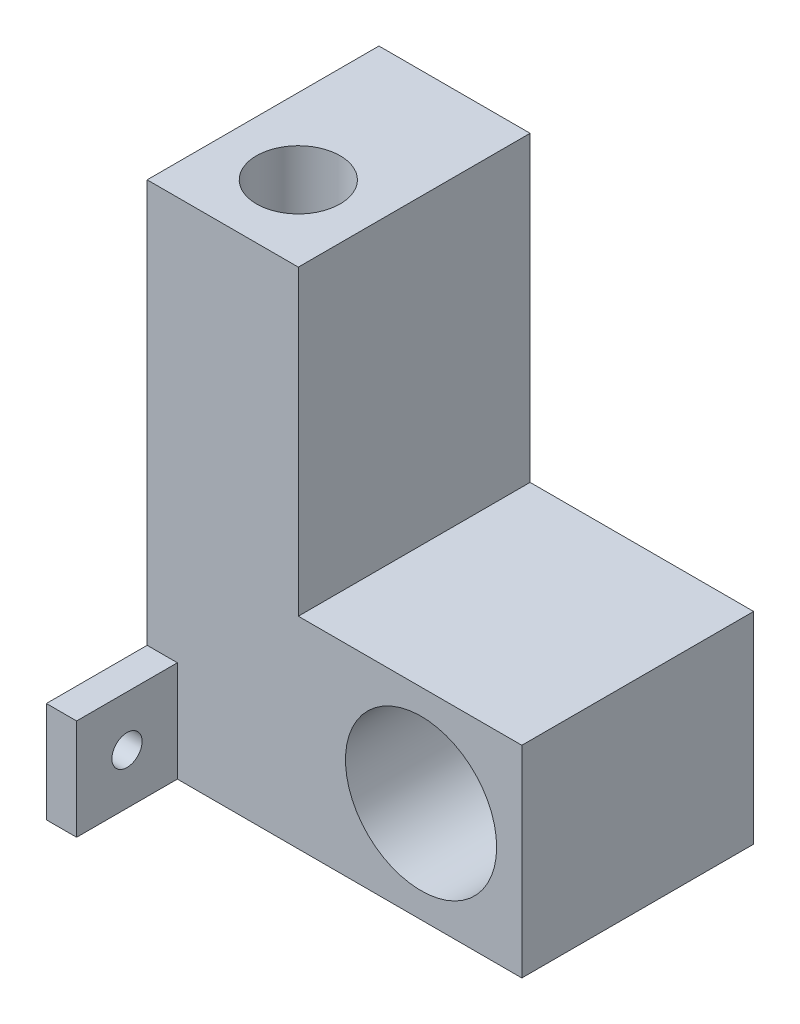
SolidWorks part; units mm, degrees
ref_plane "Front Plane" through (0, 0, 0) normal (0, 0, 1) x (1, 0, 0)
ref_plane "Top Plane" through (0, 0, 0) normal (0, 1, 0) x (1, 0, 0)
ref_plane "Right Plane" through (0, 0, 0) normal (1, 0, 0) x (0, 0, -1)
sketch "Sketch1" plane through (0, 0, 0) normal (0, 0, 1) x (1, 0, 0)
  line L0 (-12.1801, -10) -> (150.2507, -10) construction
  line L1 (0, 0) -> (200.754, 0) construction
  line L3 (0, 121.8331) -> (200.754, 121.8331) construction
  line L4 (200.754, 0) -> (200.754, 121.8331) construction
  line L5 (-12.1801, -10) -> (10, -10)
  line L6 (-12.1801, -10) -> (-12.1801, 10)
  line L7 (-12.1801, 10) -> (10, 10)
  line L8 (10, -10) -> (10, 10)
  line L10 (-12.1801, 10) -> (10, 10)
  line L18 (41.5355, 68.3037) -> (44.4022, 68.3037)
  line L19 (41.5355, 68.3037) -> (41.5355, 71.1731)
  line L20 (41.5355, 71.1731) -> (44.4022, 71.1731)
  line L21 (44.4022, 68.3037) -> (44.4022, 71.1731)
  line L22 (-12.1801, -10) -> (-27.1801, -10)
  line L23 (-12.1801, -10) -> (-12.1801, 40)
  line L24 (-12.1801, 40) -> (-27.1801, 40)
  line L25 (-27.1801, -10) -> (-27.1801, 40)
  circle A0 centre (0, 0) radius 7.5
  circle A1 centre (0, 0) radius 10
  circle A2 centre (0, 42.5) radius 32.5 construction
  circle A3 centre (14.5359, 39.9369) radius 32.5 construction
  circle A4 centre (27.3185, 32.5569) radius 32.5 construction
  circle A5 centre (36.8061, 21.25) radius 32.5 construction
  circle A6 centre (41.5355, 68.3037) radius 8
  circle A7 centre (41.5355, 68.3037) radius 14.65
  circle A8 centre (56.8061, 21.25) radius 32.5 construction
  circle A9 centre (76.8061, 21.25) radius 32.5 construction
  circle A10 centre (96.8061, 21.25) radius 32.5 construction
  circle A11 centre (116.8061, 21.25) radius 32.5 construction
  point P22 (0, 0)
  dimension "D1" = 15
  dimension "D3" = 20
  dimension "D8" = 65
  dimension "D10" = 16
  dimension "D11" = 29.3
  dimension "D2" = 0
  dimension "D4" = 10
  dimension "D5" = 15
  dimension "D6" = 50
  dimension "D7" = 10
  dimension "D12" = 5
  dimension "D9" = 4
extrude "Boss-Extrude1" add sketch "Sketch1" along normal blind 23 contours L25 L22 L6 L23 L24 | A1 L7 L6 L5 | A1 L5 L8 | A1 L8 L10 | A0
sketch "Sketch2" plane through (0, 40, 0) normal (0, 1, 0) x (1, 0, 0)
  line L0 (-12.1801, -23) -> (-27.1801, -23) construction
  line L1 (-12.1801, -23) -> (-12.1801, 0) construction
  circle A0 centre (-19.6801, -15.5) radius 4.15
  dimension "D1" = 7.5
  dimension "D3" = 8.3
  dimension "D2" = 7.5
extrude "Cut-Extrude1" cut sketch "Sketch2" against normal through all
sketch "Sketch3" plane through (-27.1801, 0, 0) normal (-1, 0, 0) x (0, 0, 1)
  line L0 (23, 40) -> (0, 40) construction
  line L1 (-10, -10) -> (33, -10)
  line L2 (-10, -10) -> (-10, 0)
  line L3 (-10, 0) -> (33, 0)
  line L4 (33, -10) -> (33, 0)
  line L5 (0, -10) -> (0, 40) construction
  line L6 (23, -10) -> (23, 40) construction
  line L7 (23, -10) -> (0, -10) construction
  circle A0 centre (-5, -5) radius 1.5
  circle A1 centre (28, -5) radius 1.5
  dimension "D5" = 3
  dimension "D6" = 3
  dimension "D7" = 5
  dimension "D8" = 5
  dimension "D9" = 5
  dimension "D10" = 5
  dimension "D1" = 40
  dimension "D2" = 10
  dimension "D3" = 10
  dimension "D4" = 0
extrude "Boss-Extrude2" add sketch "Sketch3" against normal blind 3
